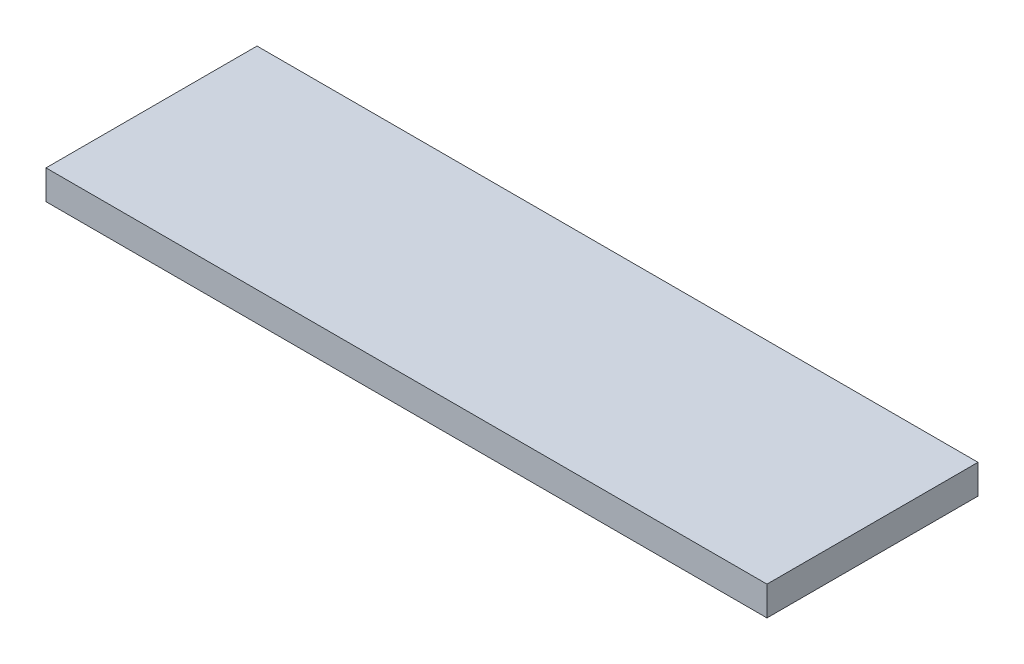
SolidWorks part; units mm, degrees
ref_plane "前视基准面" through (0, 0, 0) normal (0, 0, 1) x (1, 0, 0)
ref_plane "上视基准面" through (0, 0, 0) normal (0, 1, 0) x (1, 0, 0)
ref_plane "右视基准面" through (0, 0, 0) normal (1, 0, 0) x (0, 0, -1)
sketch "草图1" plane through (0, 0, 0) normal (0, 1, 0) x (1, 0, 0)
  line L0 (123, 0) -> (123, -72) construction
  line L1 (0, 0) -> (246, 0)
  line L2 (0, 0) -> (0, -72)
  line L3 (0, -72) -> (246, -72)
  line L4 (246, 0) -> (246, -72)
  line L9 (0, -36) -> (246, -36) construction
  dimension "D1" = 246
  dimension "D2" = 72
extrude "凸台-拉伸1" add sketch "草图1" along normal blind 10
